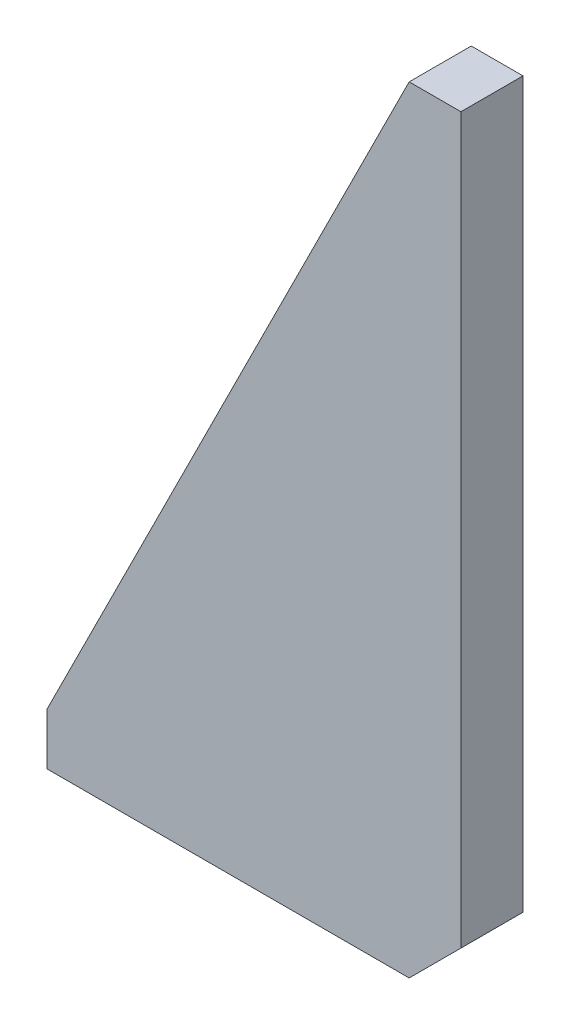
SolidWorks part; units mm, degrees
material "1.0037 (S235JR)"
ref_plane "Płaszczyzna przednia" through (0, 0, 0) normal (0, 0, 1) x (1, 0, 0)
ref_plane "Płaszczyzna górna" through (0, 0, 0) normal (0, 1, 0) x (1, 0, 0)
ref_plane "Płaszczyzna prawa" through (0, 0, 0) normal (1, 0, 0) x (0, 0, -1)
sketch "Szkic1" plane through (0, 0, 0) normal (0, 0, 1) x (1, 0, 0)
  line L0 (-80, 0) -> (-10, 0)
  line L1 (-10, 0) -> (0, 10)
  line L2 (0, 10) -> (0, 150)
  line L3 (0, 150) -> (-10, 150)
  line L4 (-10, 150) -> (-80, 10)
  line L5 (-80, 10) -> (-80, 0)
  point P1 (0, 0)
  dimension "D1" = 80
  dimension "D2" = 10
  dimension "D3" = 150
extrude "Dodanie-wyciągnięcie1" add sketch "Szkic1" along normal blind 12
